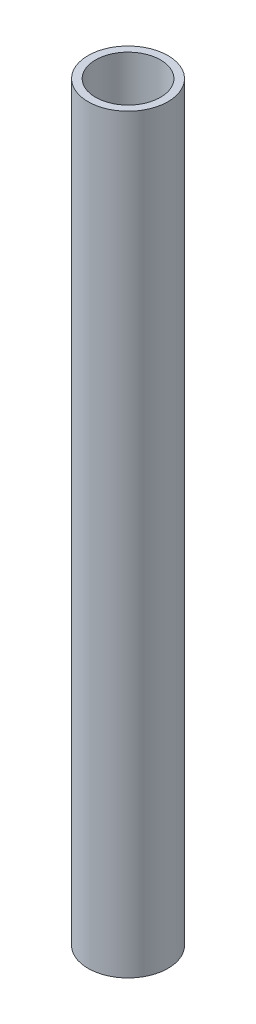
SolidWorks part; units mm, degrees
material "СТ3КП"
ref_plane "Спереди" through (0, 0, 0) normal (0, 0, 1) x (1, 0, 0)
ref_plane "Сверху" through (0, 0, 0) normal (0, 1, 0) x (1, 0, 0)
ref_plane "Справа" through (0, 0, 0) normal (1, 0, 0) x (0, 0, -1)
sketch "Эскиз1" plane through (0, 0, 0) normal (0, 1, 0) x (1, 0, 0)
  line L0 (0, 200914.2922) -> (0, -249007.8193) construction
  line L1 (-170, 9.15) -> (170, 9.15) construction
  circle B0 centre (0, -1.5) radius 8.65
  circle B1 centre (0, -1.5) radius 10.65
sketch_block_instance "Труба 21_3х2 1_2-1"
sketch_block "Труба 21_3х2 1_2" parameters "D2"=21.3, "D1"=2
extrude "Бобышка-Вытянуть1" add sketch "Эскиз1" along normal up to vertex (200 mm away)
